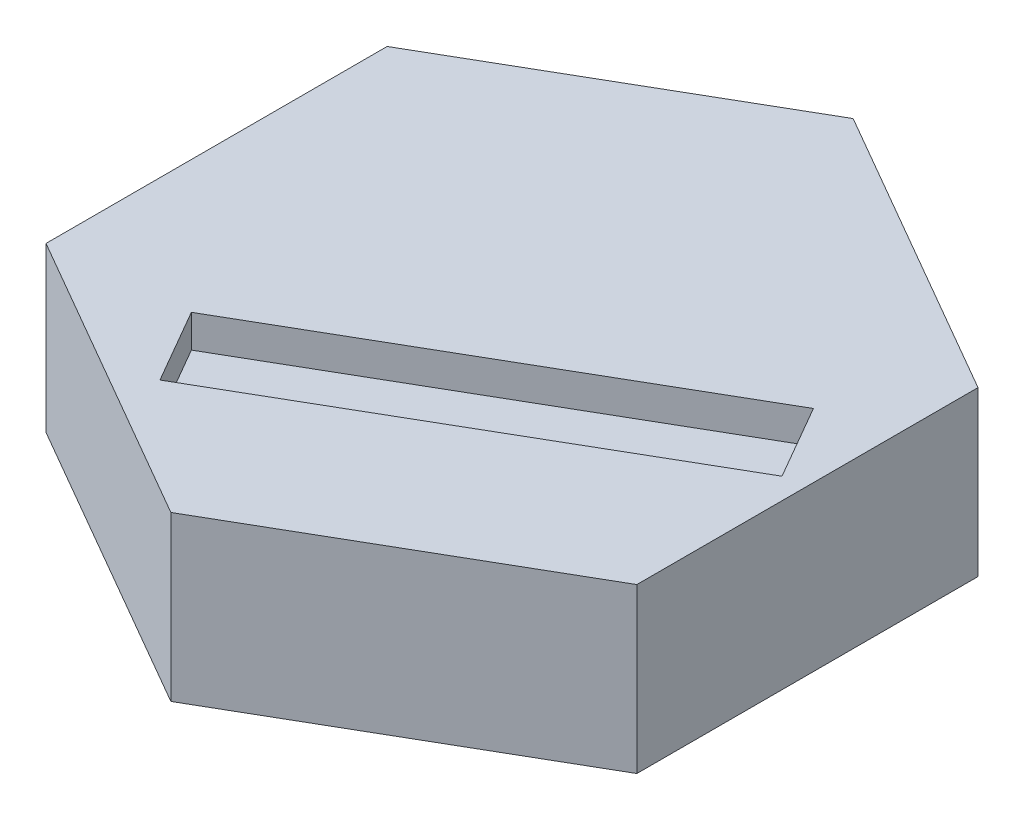
SolidWorks part; units mm, degrees
ref_plane "Plan de face" through (0, 0, 0) normal (0, 0, 1) x (1, 0, 0)
ref_plane "Plan de dessus" through (0, 0, 0) normal (0, 1, 0) x (1, 0, 0)
ref_plane "Plan de droite" through (0, 0, 0) normal (1, 0, 0) x (0, 0, -1)
sketch "Sketch1" plane through (0, 0, 0) normal (0, 1, 0) x (1, 0, 0)
  line L0 (0, 0) -> (9.025, 0) construction
  line L1 (9.025, 5.2106) -> (0, 10.4212)
  line L2 (0, 10.4212) -> (-9.025, 5.2106)
  line L3 (-9.025, 5.2106) -> (-9.025, -5.2106)
  line L4 (-9.025, -5.2106) -> (0, -10.4212)
  line L5 (0, -10.4212) -> (9.025, -5.2106)
  line L6 (9.025, -5.2106) -> (9.025, 5.2106)
  circle A0 centre (0, 0) radius 9.025 construction
  dimension "D1" = 18.05
extrude "Boss-Extrude1" add sketch "Sketch1" along normal blind 5
shell "Shell1" thickness 1
sketch "Sketch2" plane through (0, 4, 0) normal (0, -1, 0) x (1, 0, 0)
  line L6 (8.025, -4.6332) -> (8.025, 4.6332)
  line L7 (8.025, 4.6332) -> (0, 9.2665)
  line L8 (0, 9.2665) -> (-8.025, 4.6332)
  line L9 (-8.025, 4.6332) -> (-8.025, -4.6332)
  line L10 (-8.025, -4.6332) -> (0, -9.2665)
  line L11 (0, -9.2665) -> (8.025, -4.6332)
  line L12 (8.025, -4.6332) -> (8.025, 4.6332)
  line L13 (8.025, 4.6332) -> (0, 9.2665)
  line L14 (0, 9.2665) -> (-8.025, 4.6332)
  line L15 (-8.025, 4.6332) -> (-8.025, -4.6332)
  line L16 (-8.025, -4.6332) -> (0, -9.2665)
  line L17 (0, -9.2665) -> (8.025, -4.6332)
  dimension "D1" = 0
extrude "Boss-Extrude2" add sketch "Sketch2" along normal blind 2
sketch "Sketch3" plane through (0, 2, 0) normal (0, -1, 0) x (1, 0, 0)
  line L1 (-3.4, -2.45) -> (3.4, -2.45)
  line L2 (-3.4, -2.45) -> (-3.4, 2.45)
  line L3 (-3.4, 2.45) -> (3.4, 2.45)
  line L4 (3.4, -2.45) -> (3.4, 2.45)
  line L5 (-3.4, -2.45) -> (3.4, 2.45) construction
  line L6 (-3.4, 2.45) -> (3.4, -2.45) construction
  point P0 (0, 0)
  dimension "D1" = 4.9
  dimension "D2" = 6.8
extrude "Boss-Extrude3" add sketch "Sketch3" along normal blind 3.5
sketch "Sketch4" plane through (0, -1.5, 0) normal (0, -1, 0) x (1, 0, 0)
  line L0 (0, -2.1) -> (0, 2.1) construction
  line L1 (2.1, 0) -> (-2.1, 0) construction
  line L2 (2.1, -0.65) -> (2.1, 0.65)
  line L3 (-0.75, 2.1) -> (0.75, 2.1)
  line L4 (0.75, 2.1) -> (0.75, 0.65)
  line L5 (0.75, 0.65) -> (2.1, 0.65)
  line L6 (-0.75, -2.1) -> (0.75, -2.1)
  line L7 (0.75, -2.1) -> (0.75, -0.65)
  line L8 (0.75, -0.65) -> (2.1, -0.65)
  line L9 (-0.75, -2.1) -> (-0.75, -0.65)
  line L10 (-0.75, -0.65) -> (-2.1, -0.65)
  line L11 (-2.1, -0.65) -> (-2.1, 0.65)
  line L12 (-2.1, 0.65) -> (-0.75, 0.65)
  line L13 (-0.75, 0.65) -> (-0.75, 2.1)
  dimension "D1" = 1.5
  dimension "D2" = 1.3
  dimension "D3" = 4.2
extrude "Cut-Extrude1" cut sketch "Sketch4" against normal blind 3.5
sketch "Sketch5" plane through (0, 5, 0) normal (0, 1, 0) x (1, 0, 0)
  line L0 (-2.5921, -8.9493) -> (15.4793, 1.4842) construction
  line L3 (0, -10.4212) -> (9.025, -5.2106) construction
  line L5 (9.025, 5.2106) -> (0, 10.4212) construction
  text T0 "▬" font "Century Gothic" height 10
  point P2 (-10.8579, 0)
  point P3 (-14.0602, -1.6888)
  point P4 (2.8933, -4.3871)
  point P5 (-0.7853, -6.3369)
  point P8 (9.025, -1.4332)
  point P10 (3.7008, -4.0111)
  point P11 (9.025, -1.7808)
  point P12 (3.7259, 8.27)
  point P14 (-12.8274, -3.0152)
  point P15 (-14.7731, -1.8919)
  point P16 (0, 0)
  point P17 (9.025, 7.8159)
  point P18 (-12.6859, -3.0969)
  point P19 (-14.23, -2.2055)
  point P21 (-16.538, -0.873)
  point P22 (-11.0754, -4.0268)
  point P23 (-16.1351, -1.1056)
  point P24 (0, 0)
  point P25 (0, 0)
  point P26 (-12.0391, -1.3147)
  point P27 (-13.1462, -1.5915)
  point P28 (0, 0)
  point P29 (-9.4321, 0)
  point P30 (-4.953, 2.1197)
  point P31 (-6.2508, 1.2524)
  point P32 (0, 0)
  point P33 (0, 0)
  point P34 (-6.8079, 1.071)
  point P35 (-8.2115, 0.7838)
extrude "Cut-Extrude2" cut sketch "Sketch5" against normal blind 1
equation "\"s\"= 18.05mm"
equation "\"witvnsdfklgvj_thickness\"= 5mm"
equation "\"D1@Sketch1\"=\"s\""
equation "\"D1@Boss-Extrude1\"=\"witvnsdfklgvj_thickness\""
equation "\"cross_thickness\"= 3.5mm"
equation "\"D1@Boss-Extrude3\"=\"cross_thickness\""
equation "\"D1@Cut-Extrude1\"=\"cross_thickness\""
